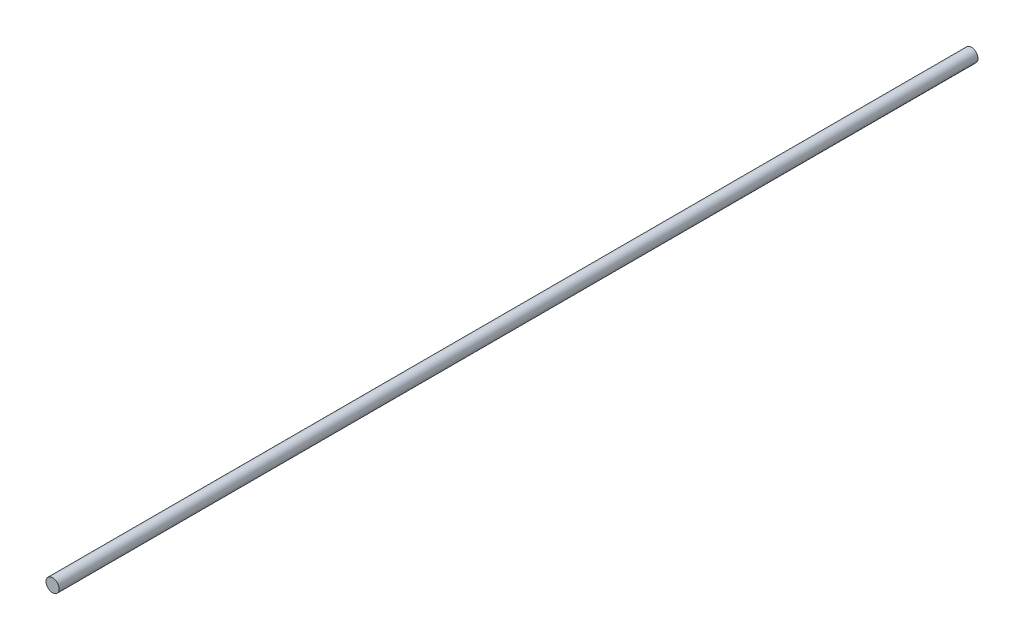
SolidWorks part; units mm, degrees
material "AISI 304"
ref_plane "Front" through (0, 0, 0) normal (0, 0, 1) x (1, 0, 0)
ref_plane "Top" through (0, 0, 0) normal (0, 1, 0) x (1, 0, 0)
ref_plane "Right" through (0, 0, 0) normal (1, 0, 0) x (0, 0, -1)
sketch "Sketch1" plane through (0, 0, 0) normal (0, 0, 1) x (1, 0, 0)
  circle A0 centre (0, 0) radius 2
  dimension "D1" = 4
extrude "Boss-Extrude1" add sketch "Sketch1" along normal blind 280
